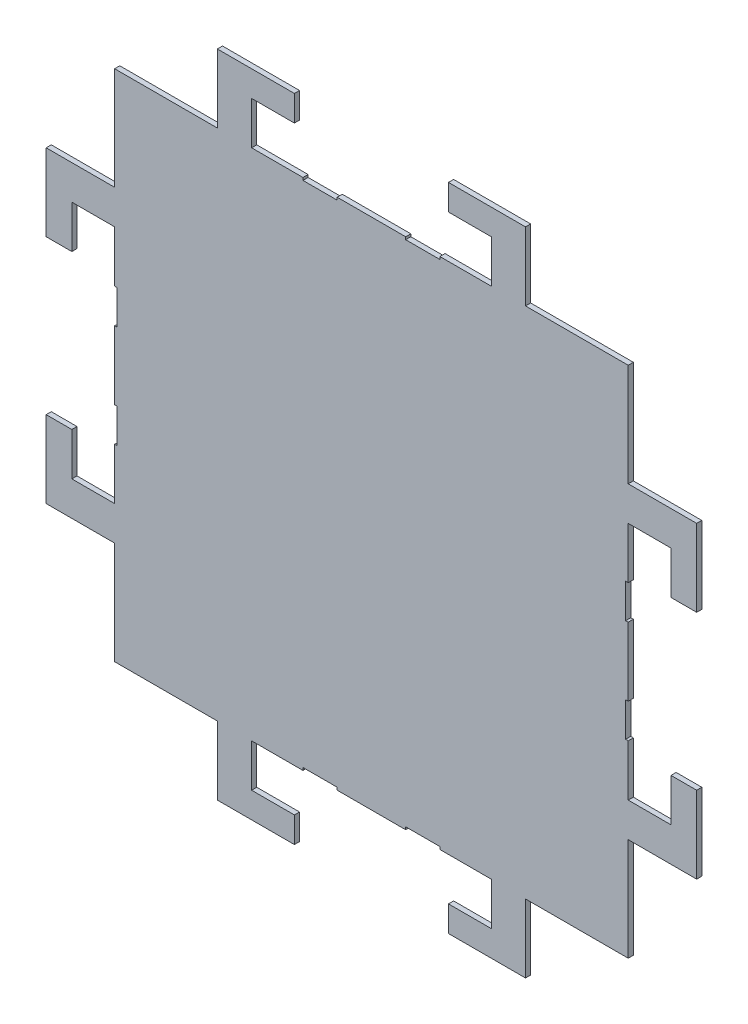
SolidWorks part; units mm, degrees
ref_plane "Plano frontal" through (0, 0, 0) normal (0, 0, 1) x (1, 0, 0)
ref_plane "Plano superior" through (0, 0, 0) normal (0, 1, 0) x (1, 0, 0)
ref_plane "Plano direito" through (0, 0, 0) normal (1, 0, 0) x (0, 0, -1)
sketch "Esboço1" plane through (0, 0, 0) normal (0, 0, 1) x (1, 0, 0)
  line L0 (-240, -190) -> (-240, -130)
  line L1 (60, -190) -> (-240, -190) construction
  line L2 (60, -190) -> (60, 110) construction
  line L3 (60, 110) -> (-240, 110) construction
  line L4 (-240, -190) -> (-240, 110) construction
  line L5 (-240, -130) -> (-280, -130)
  line L6 (-280, -130) -> (-280, -85)
  line L7 (-280, -85) -> (-265, -85)
  line L8 (-265, -85) -> (-265, -110)
  line L9 (-265, -110) -> (-240, -110)
  line L10 (-240, -110) -> (-240, -80)
  line L11 (-50, -190) -> (-50, -188.5)
  line L12 (-238.5, -80) -> (-238.5, -60)
  line L13 (-70, -190) -> (-70, -188.5)
  line L14 (-240, -60) -> (-240, -20)
  line L15 (-50, -188.5) -> (-70, -188.5)
  line L16 (-240, -20) -> (-238.5, -20)
  line L17 (-130, -190) -> (-130, -188.5)
  line L18 (-240, 0) -> (-240, 30)
  line L19 (-240, 50) -> (-280, 50)
  line L20 (-280, 50) -> (-280, 5)
  line L21 (-280, 5) -> (-265, 5)
  line L22 (-265, 5) -> (-265, 30)
  line L23 (-265, 30) -> (-240, 30)
  line L24 (-240, 50) -> (-240, 110)
  line L25 (-240, 110) -> (-180, 110)
  line L26 (-20, 110) -> (-20, 135)
  line L27 (-20, 135) -> (-45, 135)
  line L28 (-45, 135) -> (-45, 150)
  line L29 (-45, 150) -> (0, 150)
  line L30 (-160, 110) -> (-130, 110)
  line L31 (-110, -190) -> (-110, -188.5)
  line L32 (-238.5, -20) -> (-238.5, 0)
  line L33 (-110, -188.5) -> (-130, -188.5)
  line L34 (-110, 110) -> (-70, 110)
  line L35 (-240, -80) -> (-238.5, -80)
  line L36 (-238.5, 0) -> (-240, 0)
  line L37 (-240, -60) -> (-238.5, -60)
  line L38 (-50, 110) -> (-20, 110)
  line L39 (0, 150) -> (0, 110)
  line L40 (-180, 110) -> (-180, 150)
  line L41 (-180, 150) -> (-135, 150)
  line L42 (-135, 150) -> (-135, 135)
  line L43 (-135, 135) -> (-160, 135)
  line L44 (0, 110) -> (60, 110)
  line L45 (60, 110) -> (60, 50)
  line L46 (60, -130) -> (100, -130)
  line L47 (100, -130) -> (100, -85)
  line L48 (100, -85) -> (85, -85)
  line L49 (85, -85) -> (85, -110)
  line L50 (85, -110) -> (60, -110)
  line L51 (60, 30) -> (60, 0)
  line L52 (-130, 110) -> (-130, 108.5)
  line L53 (-110, 110) -> (-110, 108.5)
  line L54 (-110, 108.5) -> (-130, 108.5)
  line L55 (60, -20) -> (60, -60)
  line L56 (-70, 110) -> (-70, 108.5)
  line L57 (-70, 108.5) -> (-50, 108.5)
  line L58 (-50, 108.5) -> (-50, 110)
  line L59 (60, -80) -> (60, -110)
  line L60 (60, 50) -> (100, 50)
  line L61 (100, 50) -> (100, 5)
  line L62 (100, 5) -> (85, 5)
  line L63 (85, 5) -> (85, 30)
  line L64 (85, 30) -> (60, 30)
  line L65 (60, -130) -> (60, -190)
  line L66 (60, -190) -> (0, -190)
  line L67 (-160, 135) -> (-160, 110)
  line L68 (-180, -190) -> (-180, -230)
  line L69 (-180, -230) -> (-135, -230)
  line L70 (-135, -230) -> (-135, -215)
  line L71 (-135, -215) -> (-160, -215)
  line L72 (-20, -190) -> (-50, -190)
  line L73 (60, -20) -> (58.5, -20)
  line L74 (60, 0) -> (58.5, 0)
  line L75 (58.5, 0) -> (58.5, -20)
  line L76 (-70, -190) -> (-110, -190)
  line L77 (60, -80) -> (58.5, -80)
  line L78 (60, -60) -> (58.5, -60)
  line L79 (58.5, -60) -> (58.5, -80)
  line L80 (-130, -190) -> (-160, -190)
  line L81 (-160, -215) -> (-160, -190)
  line L82 (-20, -190) -> (-20, -215)
  line L83 (-20, -215) -> (-45, -215)
  line L84 (-45, -215) -> (-45, -230)
  line L85 (-45, -230) -> (0, -230)
  line L86 (-180, -190) -> (-240, -190)
  line L87 (0, -230) -> (0, -190)
  dimension "D1" = 300
  dimension "D2" = 300
  dimension "D3" = 60
  dimension "D4" = 60
  dimension "D7" = 1.5
  dimension "D8" = 40
  dimension "D9" = 45
  dimension "D10" = 45
  dimension "D11" = 40
  dimension "D12" = 15
  dimension "D13" = 30
  dimension "D14" = 30
  dimension "D15" = 1.5
  dimension "D16" = 20
  dimension "D17" = 1.5
  dimension "D18" = 20
  dimension "D19" = 40
  dimension "D20" = 15
  dimension "D21" = 60
  dimension "D22" = 60
  dimension "D23" = 60
  dimension "D24" = 25
  dimension "D25" = 30
  dimension "D26" = 30
  dimension "D27" = 25
  dimension "D28" = 15
  dimension "D29" = 45
  dimension "D30" = 40
  dimension "D31" = 45
  dimension "D32" = 15
  dimension "D33" = 25
  dimension "D34" = 1.5
  dimension "D35" = 20
  dimension "D36" = 40
  dimension "D37" = 1.5
  dimension "D38" = 1.5
  dimension "D39" = 40
  dimension "D40" = 45
  dimension "D41" = 15
  dimension "D42" = 60
  dimension "D43" = 25
  dimension "D44" = 40
  dimension "D45" = 30
  dimension "D46" = 45
  dimension "D47" = 1.5
  dimension "D48" = 20
  dimension "D49" = 40
  dimension "D50" = 1.5
  dimension "D51" = 20
  dimension "D52" = 15
  dimension "D53" = 25
  dimension "D54" = 40
  dimension "D55" = 45
  dimension "D56" = 60
  dimension "D57" = 60
  dimension "D58" = 30
  dimension "D59" = 30
  dimension "D60" = 15
  dimension "D61" = 25
  dimension "D62" = 1.5
  dimension "D63" = 20
  dimension "D64" = 25
  dimension "D65" = 45
  dimension "D66" = 1.5
  dimension "D67" = 1.5
  dimension "D68" = 1.5
extrude "Ressalto-extrusão1" add sketch "Esboço1" along normal blind 3
